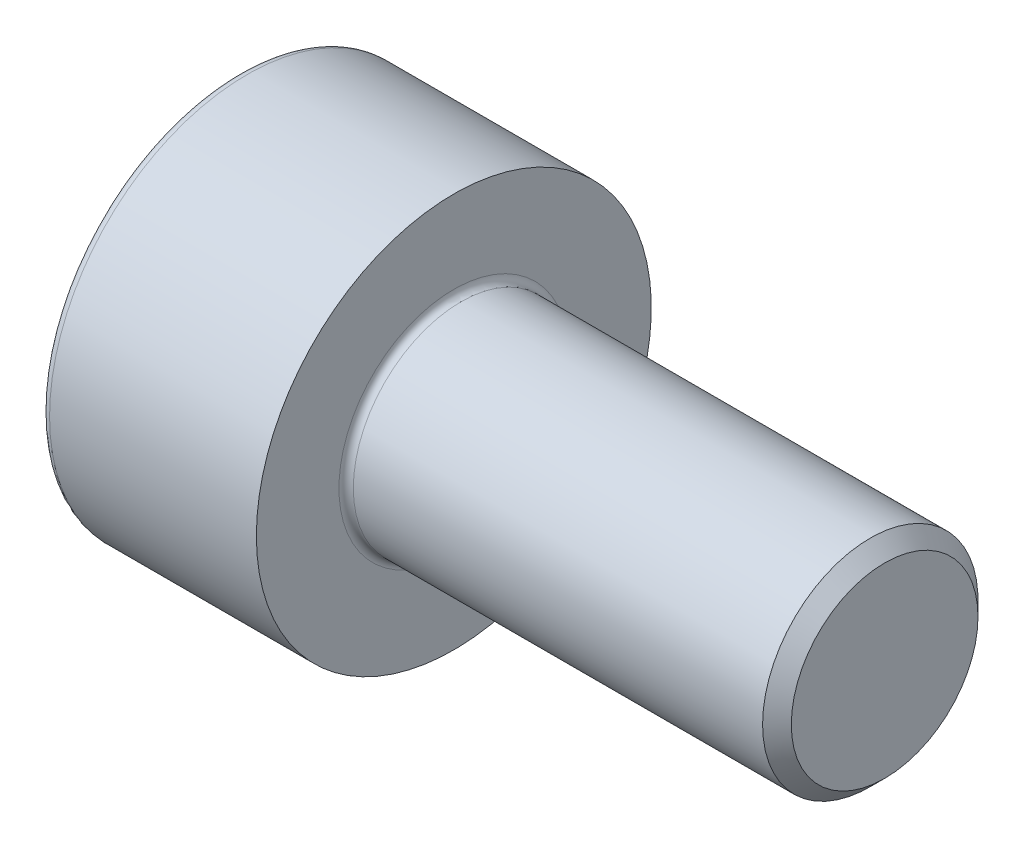
SolidWorks part; units mm, degrees
ref_plane "Front Plane" through (0, 0, 0) normal (0, 0, 1) x (1, 0, 0)
ref_plane "Top Plane" through (0, 0, 0) normal (0, 1, 0) x (1, 0, 0)
ref_plane "Right Plane" through (0, 0, 0) normal (1, 0, 0) x (0, 0, -1)
sketch "Sketch1" plane through (0, 0, 0) normal (0, 0, 1) x (1, 0, 0)
  line L0 (0, 0) -> (0, 2.75)
  line L1 (0, 2.75) -> (3, 2.75)
  line L2 (3, 2.75) -> (3, 0)
  line L3 (0, 0) -> (4.2799, 0) construction
  line L4 (3, 0) -> (9, 0)
  line L5 (9, 0) -> (9, 1.5)
  line L6 (9, 1.5) -> (3, 1.5)
  dimension "D1" = 6
  dimension "D2" = 3
  dimension "D3" = 2.75
  dimension "D4" = 1.5
revolve "Revolve1" add sketch "Sketch1" angle 360 about L3
fillet "Fillet1" radius 0.1 1 edges at (3, 0, 1.5)
fillet "Fillet2" radius 0.12 1 edges at (0, 0, 2.75)
chamfer "Chamfer1" distance 0.2 angle 45 1 edges at (9, 0, 1.5)
sketch "Sketch2" plane through (0, 0, 0) normal (-1, 0, 0) x (0, 0, 1)
  line L1 (0, 1.4434) -> (-1.25, 0.7217)
  line L2 (-1.25, 0.7217) -> (-1.25, -0.7217)
  line L3 (-1.25, -0.7217) -> (0, -1.4434)
  line L4 (0, -1.4434) -> (1.25, -0.7217)
  line L5 (1.25, -0.7217) -> (1.25, 0.7217)
  line L6 (1.25, 0.7217) -> (0, 1.4434)
  circle A0 centre (0, 0) radius 1.25 construction
extrude "Extrude1" cut sketch "Sketch2" against normal blind 1
